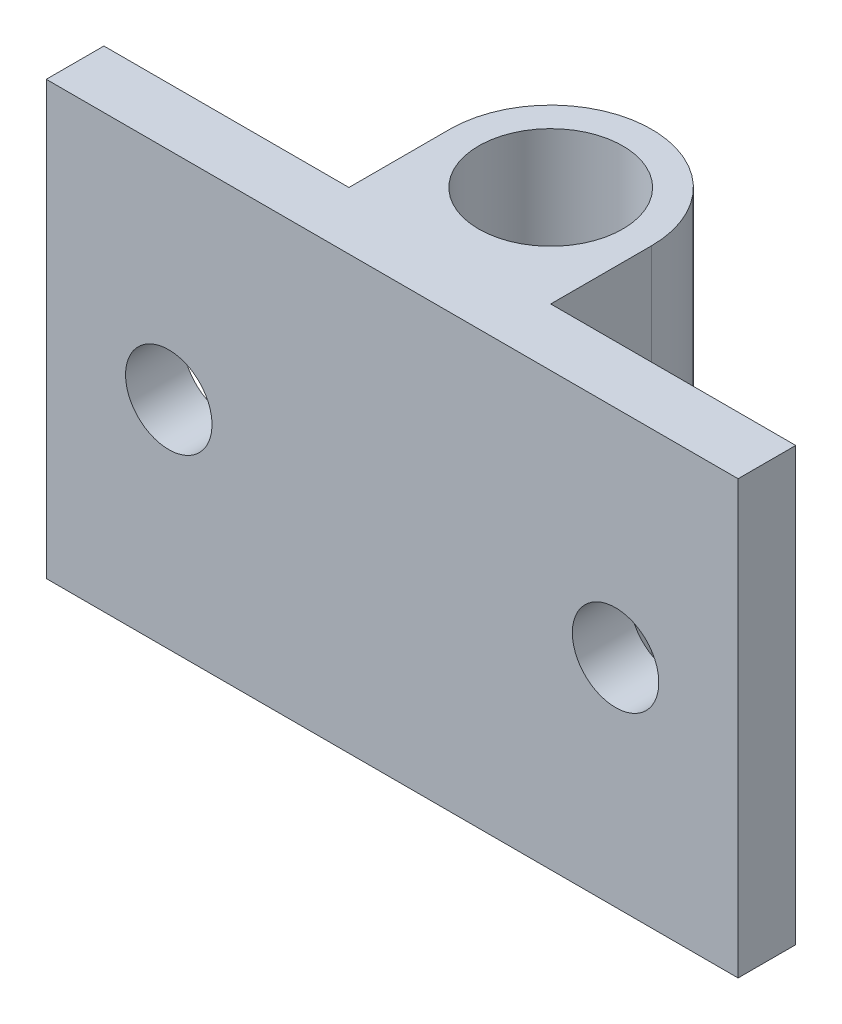
SolidWorks part; units mm, degrees
ref_plane "Front" through (0, 0, 0) normal (0, 0, 1) x (1, 0, 0)
ref_plane "Top" through (0, 0, 0) normal (0, 1, 0) x (1, 0, 0)
ref_plane "Right" through (0, 0, 0) normal (1, 0, 0) x (0, 0, -1)
sketch "Sketch1" plane through (0, 0, 0) normal (0, 1, 0) x (1, 0, 0)
  line L0 (0, 0) -> (0, -5.5)
  line L1 (0, -5.5) -> (12, -5.5)
  line L2 (0, -5.5) -> (-12, -5.5)
  line L3 (-12, -5.5) -> (-12, -3.5)
  line L4 (0, 2.5) -> (0, 3.5)
  line L5 (-2.5, 0) -> (-3.5, 0)
  line L6 (2.5, 0) -> (3.5, 0)
  line L7 (-3.5, 0) -> (-3.5, -3.5)
  line L8 (-3.5, -3.5) -> (-12, -3.5)
  line L9 (3.5, 0) -> (3.5, -3.5)
  line L10 (12, -5.5) -> (12, -3.5)
  line L11 (12, -3.5) -> (3.5, -3.5)
  circle A0 centre (0, 0) radius 2.5
  arc A1 (-3.5, 0) -> (3.5, 0) centre (0, 0) cw
  dimension "D1" = 12
  dimension "D3" = 5.5
  dimension "D4" = 2
  dimension "D2" = 12
  dimension "D5" = 1
  dimension "D6" = 1
  dimension "D7" = 1
extrude "Boss-Extrude1" add sketch "Sketch1" along normal blind 15 contours A1 L4 A0 L6 | A1 L5 A0 L4 | A0 L5 L7 L8 L3 L2 L0 | A0 L0 L1 L10 L11 L9 L6
sketch "Sketch2" plane through (0, 0, 3.5) normal (0, 0, -1) x (-1, 0, 0)
  line L0 (7.75, 15) -> (7.75, 0)
  line L1 (3.5, 15) -> (12, 15) construction
  line L2 (3.5, 0) -> (12, 0) construction
  line L3 (-7.75, 15) -> (-7.75, 0)
  line L4 (-12, 15) -> (-3.5, 15) construction
  line L5 (-12, 0) -> (-3.5, 0) construction
  circle A0 centre (7.75, 7.5) radius 1.5
  circle A1 centre (-7.75, 7.5) radius 1.5
extrude "Cut-Extrude1" cut sketch "Sketch2" against normal through all contours L3 A1 | L3 A1 | L0 A0 | L0 A0
